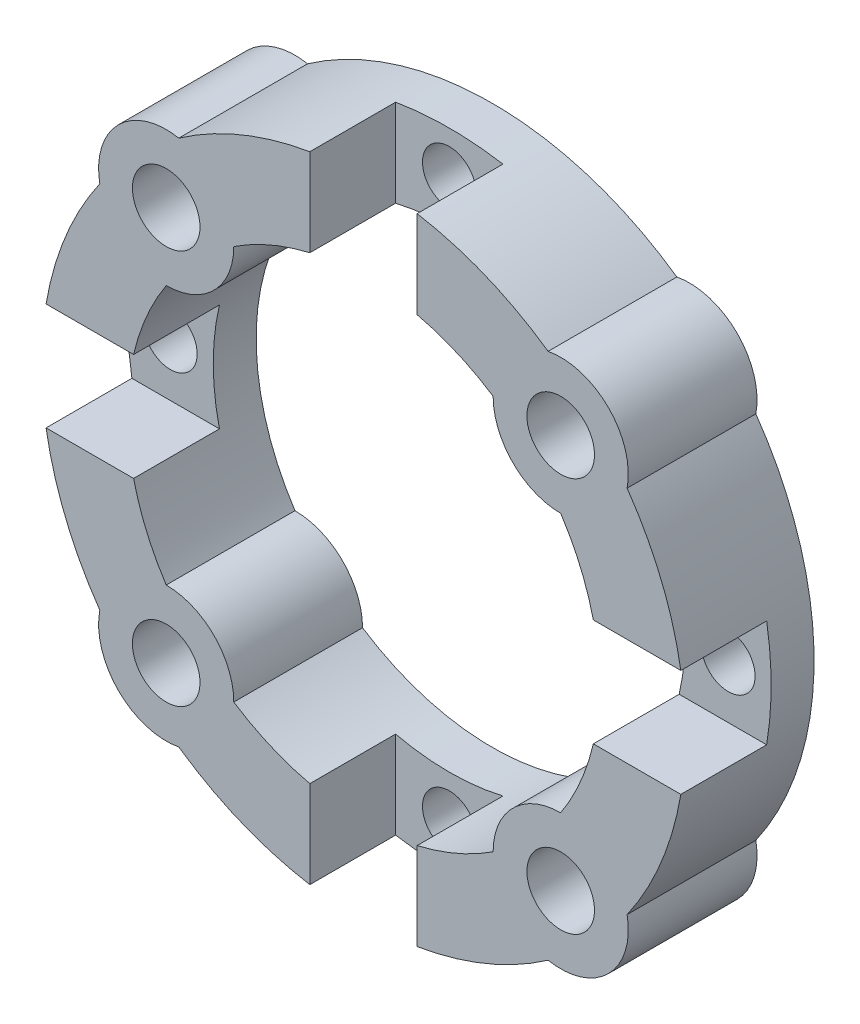
SolidWorks part; units mm, degrees
ref_plane "Front Plane" through (0, 0, 0) normal (0, 0, 1) x (1, 0, 0)
ref_plane "Top Plane" through (0, 0, 0) normal (0, 1, 0) x (1, 0, 0)
ref_plane "Right Plane" through (0, 0, 0) normal (1, 0, 0) x (0, 0, -1)
sketch "Sketch1" plane through (0, 0, 0) normal (0, 0, 1) x (1, 0, 0)
  circle A0 centre (0, 0) radius 19.05
  circle A1 centre (0, 0) radius 13.97
  dimension "D1" = 38.1
  dimension "D2" = 5.08
extrude "Boss-Extrude1" add sketch "Sketch1" along normal blind 7.62
sketch "Sketch2" plane through (0, 0, 7.62) normal (0, 0, 1) x (1, 0, 0)
  circle A0 centre (0, 0) radius 16.51 construction
  circle A1 centre (0, 16.51) radius 1.5875
  circle A2 centre (16.51, 0) radius 1.5875
  circle A3 centre (0, -16.51) radius 1.5875
  circle A4 centre (-16.51, 0) radius 1.5875
  dimension "D1" = 33.02
  dimension "D2" = 3.175
  dimension "D3" = 3.175
  dimension "D4" = 3.175
  dimension "D5" = 3.175
extrude "Cut-Extrude1" cut sketch "Sketch2" against normal through all
sketch "Sketch3" plane through (0, 0, 7.62) normal (0, 0, 1) x (1, 0, 0)
  line L1 (-31.7795, -3.175) -> (31.7795, -3.175)
  line L2 (-31.7795, -3.175) -> (-31.7795, 3.175)
  line L3 (-31.7795, 3.175) -> (31.7795, 3.175)
  line L4 (31.7795, -3.175) -> (31.7795, 3.175)
  line L5 (-31.7795, -3.175) -> (31.7795, 3.175) construction
  line L6 (-31.7795, 3.175) -> (31.7795, -3.175) construction
  line L7 (3.175, -27.6971) -> (-3.175, -27.6971)
  line L8 (3.175, -27.6971) -> (3.175, 27.6971)
  line L9 (3.175, 27.6971) -> (-3.175, 27.6971)
  line L10 (-3.175, -27.6971) -> (-3.175, 27.6971)
  line L11 (3.175, -27.6971) -> (-3.175, 27.6971) construction
  line L12 (3.175, 27.6971) -> (-3.175, -27.6971) construction
  point P0 (0, 0)
  point P7 (0, 0)
  circle M3 centre (0, 16.51) radius 1.5875
  circle M4 centre (16.51, 0) radius 1.5875
  circle M5 centre (0, -16.51) radius 1.5875
  circle M6 centre (-16.51, 0) radius 1.5875
  circle M7 centre (0, 0) radius 19.05
  circle M8 centre (0, 0) radius 13.97
  dimension "D1" = 6.35
  dimension "D2" = 6.35
extrude "Cut-Extrude2" cut sketch "Sketch3" against normal blind 5.08 contours L3 L1 M7 M8 M6 | L10 L8 M7 M8 M5 | L3 L1 M8 M7 M4 | L10 L8 M8 M7 M3
sketch "Sketch4" plane through (0, 0, 7.62) normal (0, 0, 1) x (1, 0, 0)
  line L0 (0, 0) -> (-11.6743, 11.6743) construction
  line L1 (0, 0) -> (-16.51, 0) construction
  circle A0 centre (0, 0) radius 16.51 construction
  circle A1 centre (-11.6743, 11.6743) radius 1.5
  dimension "D1" = 33.02
  dimension "D3" = 3
  dimension "D2" = 45
extrude "Cut-Extrude3" cut sketch "Sketch4" against normal through all
sketch "Sketch5" plane through (0, 0, 7.62) normal (0, 0, 1) x (1, 0, 0)
  circle A0 centre (-11.6743, 11.6743) radius 2
  dimension "D1" = 4
extrude "Cut-Extrude4" cut sketch "Sketch5" against normal blind 5.7
sketch "Sketch6" plane through (0, 0, 7.62) normal (0, 0, 1) x (1, 0, 0)
  circle A0 centre (-11.6743, 11.6743) radius 4
  circle A1 centre (-11.6743, 11.6743) radius 2
  dimension "D1" = 2
extrude "Boss-Extrude2" add sketch "Sketch6" against normal up to surface (7.62 mm away) up to face at (-10.1743, 11.6743, 0)
pattern_circular "CirPattern1" count 4 every 90 about axis through (0, 0, 0) along (0, 0, 1) of "Cut-Extrude3", "Cut-Extrude4", "Boss-Extrude2"
